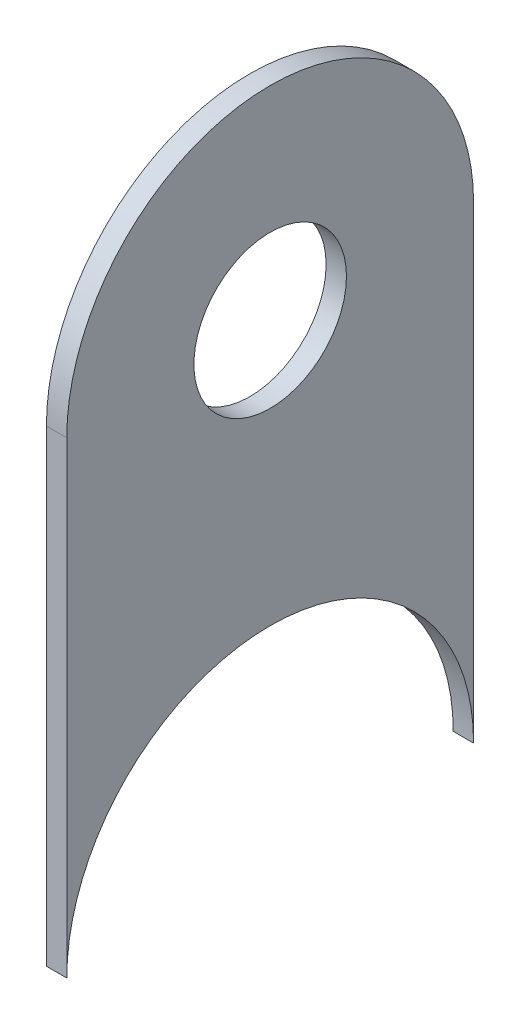
SolidWorks part; units mm, degrees
ref_plane "Front Plane" through (0, 0, 0) normal (0, 0, 1) x (1, 0, 0)
ref_plane "Top Plane" through (0, 0, 0) normal (0, 1, 0) x (1, 0, 0)
ref_plane "Right Plane" through (0, 0, 0) normal (1, 0, 0) x (0, 0, -1)
sketch "Sketch1" plane through (0, 0, 0) normal (1, 0, 0) x (0, 0, -1)
  line L0 (-12.7, 0) -> (-12.7, -29.21)
  line L1 (12.7, 0) -> (12.7, -29.21)
  arc A0 (12.7, 0) -> (-12.7, 0) centre (0, 0) ccw
  circle A1 centre (0, 0) radius 4.7625
  arc A2 (12.7, -29.21) -> (-12.7, -29.21) centre (0, -29.21) ccw
  dimension "D1" = 25.4
  dimension "D2" = 9.525
  dimension "D3" = 16.51
extrude "Boss-Extrude1" add sketch "Sketch1" along normal blind 1.27
